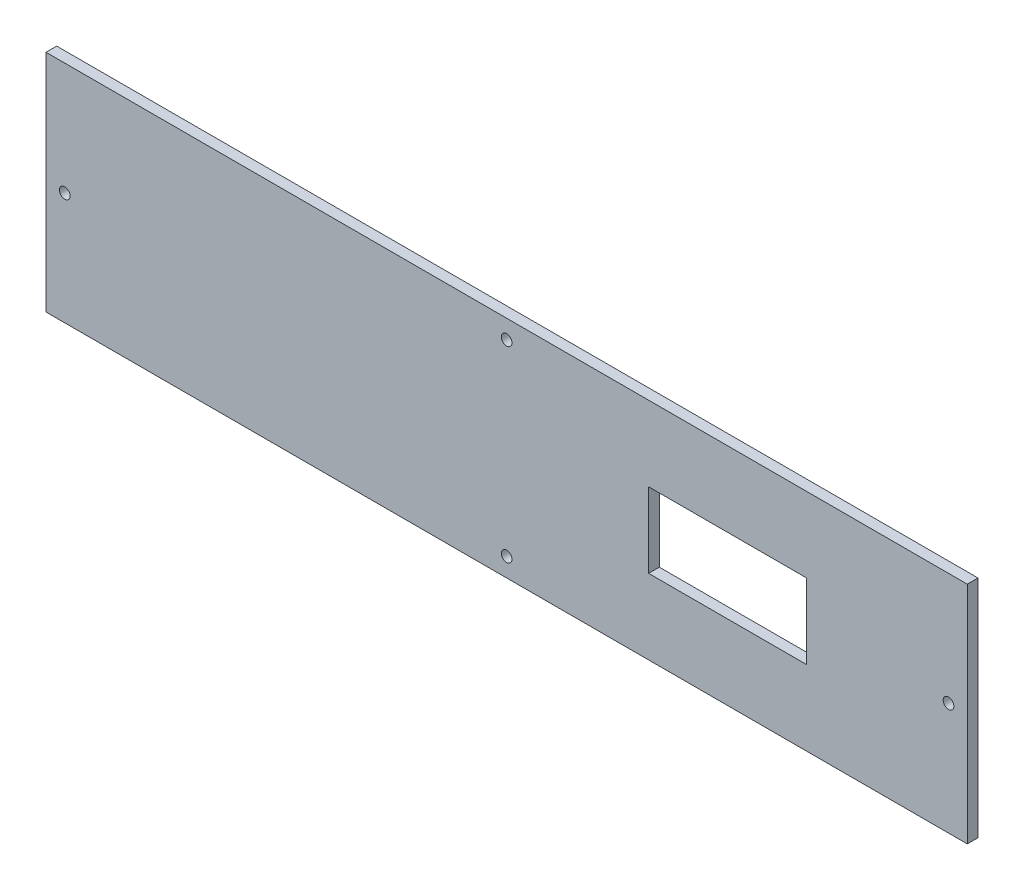
SolidWorks part; units mm, degrees
ref_plane "Piano frontale" through (0, 0, 0) normal (0, 0, 1) x (1, 0, 0)
ref_plane "Piano superiore" through (0, 0, 0) normal (0, 1, 0) x (1, 0, 0)
ref_plane "Piano destro" through (0, 0, 0) normal (1, 0, 0) x (0, 0, -1)
sketch "Schizzo1" plane through (0, 0, 0) normal (0, 0, 1) x (1, 0, 0)
  line L0 (0, 0) -> (0, 84)
  line L1 (0, 84) -> (344, 84)
  line L2 (344, 84) -> (344, 0)
  line L3 (344, 0) -> (0, 0)
  line L4 (0, 42) -> (344, 42) construction
  line L5 (172, 42) -> (172, 123.488) construction
  line L6 (225, 56) -> (225, 28)
  line L7 (225, 28) -> (284, 28)
  line L8 (284, 28) -> (284, 56)
  line L9 (284, 56) -> (225, 56)
  circle A0 centre (7, 42) radius 2
  circle A1 centre (172, 77) radius 2
  circle A2 centre (172, 7) radius 2
  circle A3 centre (337, 42) radius 2
  dimension "D3" = 7
  dimension "D4" = 7
  dimension "D6" = 4
  dimension "D1" = 84
  dimension "D2" = 344
  dimension "D5" = 60
  dimension "D7" = 59
  dimension "D8" = 28
extrude "Estrusione-Estrusione1" add sketch "Schizzo1" along normal blind 4
